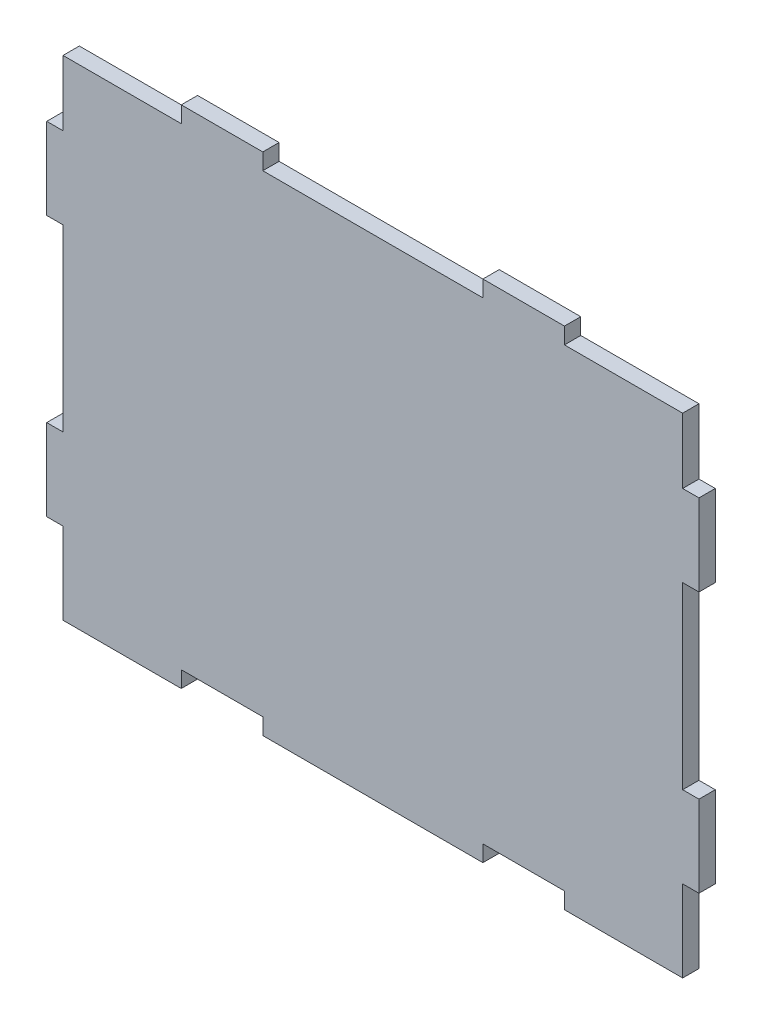
SolidWorks part; units mm, degrees
ref_plane "Front Plane" through (0, 0, 0) normal (0, 0, 1) x (1, 0, 0)
ref_plane "Top Plane" through (0, 0, 0) normal (0, 1, 0) x (1, 0, 0)
ref_plane "Right Plane" through (0, 0, 0) normal (1, 0, 0) x (0, 0, -1)
sketch "Sketch1" plane through (0, 0, 0) normal (0, 0, 1) x (1, 0, 0)
  line L0 (-96.52, -88.9) -> (-96.52, -63.5) construction
  line L1 (96.52, -88.9) -> (-96.52, -88.9)
  line L2 (96.52, -88.9) -> (96.52, 63.5)
  line L3 (96.52, 63.5) -> (-96.52, 63.5)
  line L4 (-96.52, -88.9) -> (-96.52, 63.5)
  line L5 (96.52, -88.9) -> (96.52, -63.5) construction
  line L6 (-34.29, 63.5) -> (34.29, 63.5) construction
  line L7 (96.52, -88.9) -> (59.69, -88.9)
  line L8 (59.69, 63.5) -> (34.29, 63.5)
  line L9 (59.69, 63.5) -> (59.69, 68.58)
  line L10 (59.69, 68.58) -> (34.29, 68.58)
  line L11 (34.29, 63.5) -> (34.29, 68.58)
  line L12 (-34.29, 63.5) -> (-59.69, 63.5)
  line L13 (-34.29, 63.5) -> (-34.29, 68.58)
  line L14 (-34.29, 68.58) -> (-59.69, 68.58)
  line L15 (-59.69, 63.5) -> (-59.69, 68.58)
  line L16 (59.69, -88.9) -> (34.29, -88.9)
  line L17 (59.69, -88.9) -> (59.69, -83.82)
  line L18 (59.69, -83.82) -> (34.29, -83.82)
  line L19 (34.29, -88.9) -> (34.29, -83.82)
  line L20 (-34.29, -88.9) -> (-59.69, -88.9)
  line L21 (-34.29, -88.9) -> (-34.29, -83.82)
  line L22 (-34.29, -83.82) -> (-59.69, -83.82)
  line L23 (-59.69, -88.9) -> (-59.69, -83.82)
  line L24 (59.69, -83.82) -> (96.52, -83.82)
  line L25 (-59.69, -83.82) -> (-96.52, -83.82)
  dimension "D1" = 5.08
  dimension "D2" = 25.4
  dimension "D3" = 36.83
extrude "Boss-Extrude1" add sketch "Sketch1" along normal blind 5.08 contours L25 L22 L21 L1 L19 L18 L24 L2 L3 L4 | L24 L17 L1 L2 | L23 L25 L4 L1 | L11 L3 L9 L10 | L14 L15 L12 L13
sketch "Sketch2" plane through (0, 0, 5.08) normal (0, 0, 1) x (1, 0, 0)
  line L0 (96.52, -88.9) -> (96.52, 63.5) construction
  line L1 (101.6, -63.5) -> (96.52, -63.5)
  line L2 (101.6, -63.5) -> (101.6, -38.1)
  line L3 (101.6, -38.1) -> (96.52, -38.1)
  line L4 (96.52, -63.5) -> (96.52, -38.1)
  line L5 (96.52, -38.1) -> (101.6, -38.1) construction
  line L6 (96.52, 17.78) -> (101.6, 17.78) construction
  line L7 (101.6, 43.18) -> (96.52, 43.18)
  line L8 (101.6, 43.18) -> (101.6, 17.78)
  line L9 (101.6, 17.78) -> (96.52, 17.78)
  line L10 (96.52, 43.18) -> (96.52, 17.78)
  line L11 (-96.52, -88.9) -> (-96.52, 63.5) construction
  line L12 (-101.6, -63.5) -> (-96.52, -63.5)
  line L13 (-101.6, -63.5) -> (-101.6, -38.1)
  line L14 (-101.6, -38.1) -> (-96.52, -38.1)
  line L15 (-96.52, -63.5) -> (-96.52, -38.1)
  line L16 (-101.6, -38.1) -> (-96.52, -38.1) construction
  line L17 (-101.6, 43.18) -> (-96.52, 43.18) construction
  line L18 (-101.6, 17.78) -> (-96.52, 17.78)
  line L19 (-101.6, 17.78) -> (-101.6, 43.18)
  line L20 (-101.6, 43.18) -> (-96.52, 43.18)
  line L21 (-96.52, 17.78) -> (-96.52, 43.18)
extrude "Boss-Extrude2" add sketch "Sketch2" against normal blind 5.08
